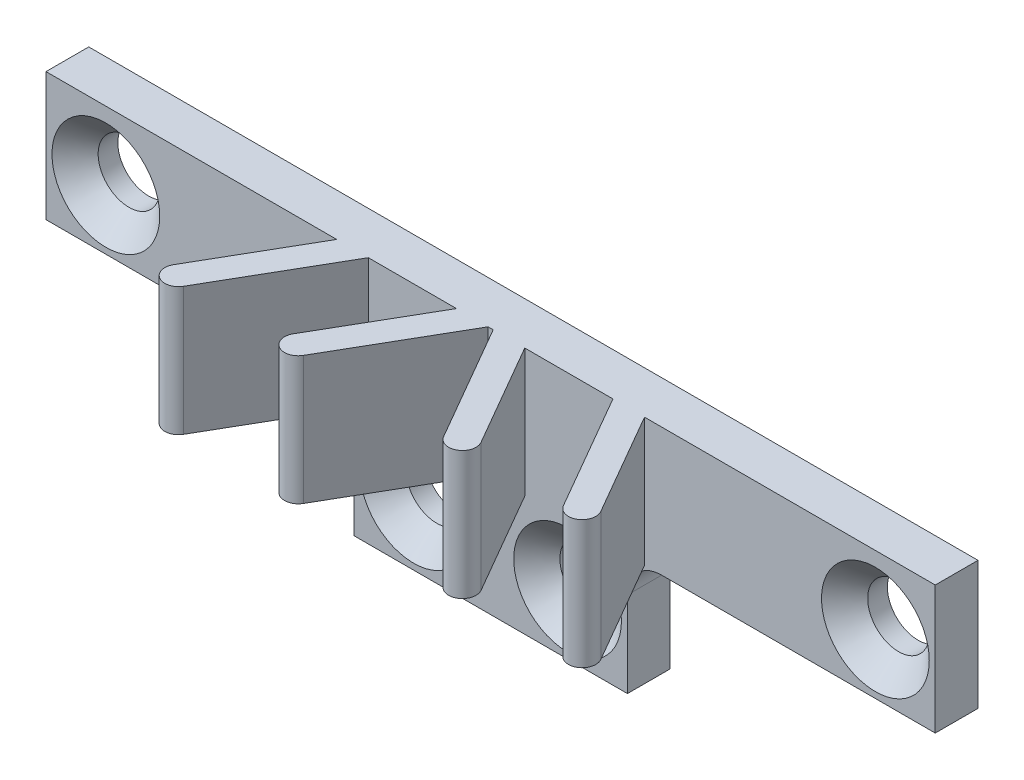
SolidWorks part; units mm, degrees
material "POLYURETHANE (11671)"
ref_plane "Front Plane" through (0, 0, 0) normal (0, 0, 1) x (1, 0, 0)
ref_plane "Top Plane" through (0, 0, 0) normal (0, 1, 0) x (1, 0, 0)
ref_plane "Right Plane" through (0, 0, 0) normal (1, 0, 0) x (0, 0, -1)
sketch "Sketch1" plane through (0, 0, 0) normal (0, 0, 1) x (1, 0, 0)
  line L20 (26, 7.25) -> (26, -0.25)
  line L21 (8, -7.25) -> (-8, -7.25)
  line L22 (-8, -7.25) -> (-8, -0.25)
  line L23 (-8, -0.25) -> (-26, -0.25)
  line L24 (-26, -0.25) -> (-26, 7.25)
  line L25 (-26, 7.25) -> (26, 7.25)
  line L27 (8, -7.25) -> (8, -0.25)
  line L28 (8, -0.25) -> (26, -0.25)
  line L29 (0, -55) -> (0, 55) construction
  line L30 (0, -7.25) -> (0, 7.25) construction
  line L32 (55, 0) -> (-55, 0) construction
  point P14 (0, 0)
  point P15 (0, -7.25)
  dimension "D1" = 52
  dimension "D2" = 7.5
  dimension "D3" = 16
  dimension "D4" = 7
extrude "Boss-Extrude1" add sketch "Sketch1" along normal mid plane 10
sketch "Sketch2" plane through (0, 0, 5) normal (0, 0, 1) x (1, 0, 0)
  line L5 (-8, -0.25) -> (8, -0.25)
  line L6 (-8, -0.25) -> (-8, -7.25)
  line L7 (-8, -7.25) -> (8, -7.25)
  line L8 (8, -0.25) -> (8, -7.25)
  line L13 (8, -0.25) -> (26, -0.25) construction
  line L14 (26, 7.25) -> (19, 7.25)
  line L15 (26, 7.25) -> (26, -0.25)
  line L16 (26, -0.25) -> (19, -0.25)
  line L17 (19, 7.25) -> (19, -0.25)
  line L18 (-8, -7.25) -> (8, -7.25) construction
  line L19 (8, -7.25) -> (8, -0.25) construction
  line L20 (-26, -0.25) -> (-8, -0.25) construction
  line L21 (-26, 7.25) -> (-19, 7.25)
  line L22 (-26, 7.25) -> (-26, -0.25)
  line L23 (-26, -0.25) -> (-19, -0.25)
  line L24 (-19, 7.25) -> (-19, -0.25)
  dimension "D1" = 7
extrude "Cut-Extrude1" cut sketch "Sketch2" against normal blind 7.5
hole_wizard "CSK for M3 Countersunk Flat Head Screw1" positions "Sketch5" profile "Sketch4" countersink size "M3" standard "ISO"
sketch "Sketch5" plane through (0, 0, -2.5) normal (0, 0, 1) x (1, 0, 0)
  line L1 (-8, -7.25) -> (8, -7.25) construction
  line L2 (0, -55) -> (0, 55) construction
  line L3 (-26, 7.25) -> (-26, -0.25) construction
  line L4 (26, -0.25) -> (26, 7.25) construction
  line L5 (-26, -0.25) -> (-19, -0.25) construction
  point P4 (-4.5, -3.75)
  point P6 (4.5, -3.75)
  point P19 (-22.5, 3.25)
  point P21 (22.5, 3.25)
  dimension "D2" = 3.5
  dimension "D3" = 4.5
  dimension "D4" = 9
  dimension "D1" = 3.5
  dimension "D5" = 3.5
  dimension "D6" = 3.5
sketch "Sketch4" plane through (-4.5, -3.75, -2.5) normal (1, 0, 0) x (0, -1, 0)
  line L0 (0, 0) -> (0, 6.0815)
  line L1 (0, 6.0815) -> (1.8, 5)
  line L2 (1.8, 5) -> (1.8, 1.35)
  line L3 (1.8, 1.35) -> (3.15, 0)
  line L5 (3.15, 0) -> (0, 0)
  line L6 (-1.8, 1.35) -> (-3.15, 0) construction
  line L10 (0, 6.0815) -> (-1.8, 5) construction
  line L11 (0, -6.35) -> (0, 107.95) construction
  dimension "Hole Dia." = 3.6
  dimension "Hole Depth" = 5
  dimension "Near C'Sink Dia." = 6.3
  dimension "Near C'Sink Angle" = 90
  dimension "Drill Angle" = 118
fillet "Fillet1" radius 2 2 edges at (8, -0.25, -3.75) (-8, -0.25, -3.75)
sketch "Sketch6" plane through (0, 7.25, 0) normal (0, 1, 0) x (1, 0, 0)
  line L1 (12.4932, -3.5505) -> (13.3301, -5) construction
  line L8 (13.3301, -5) -> (11.4826, -5)
  line L9 (12.4932, -3.5505) -> (9, 2.5)
  line L35 (12.4932, -3.5505) -> (11.1076, -4.3505) construction
  line L36 (11.1076, -4.3505) -> (11.4826, -5) construction
  line L37 (19, -5) -> (-19, -5) construction
  line L38 (9, 2.5) -> (7.1525, 2.5) construction
  line L39 (7.1525, 2.5) -> (11.1076, -4.3505)
  line L40 (26, 2.5) -> (19, 2.5) construction
  line L41 (9, 2.5) -> (19, 2.5)
  line L42 (19, 2.5) -> (19, -5)
  line L43 (19, -5) -> (13.3301, -5)
  line L45 (1.9975, 2.5) -> (5.4908, -3.5505)
  line L46 (5.4908, -3.5505) -> (4.1051, -4.3505) construction
  line L47 (4.1051, -4.3505) -> (4.4801, -5) construction
  line L48 (4.1051, -4.3505) -> (0.15, 2.5)
  line L50 (-4.1051, -4.3505) -> (-5.4908, -3.5505) construction
  line L51 (-5.4908, -3.5505) -> (-1.9975, 2.5)
  line L52 (-4.1051, -4.3505) -> (-4.4801, -5)
  line L54 (0, -55) -> (0, 55) construction
  line L55 (11.4826, -5) -> (4.4801, -5)
  line L56 (19, 2.5) -> (19, -5) construction
  line L57 (7.1525, 2.5) -> (1.9975, 2.5)
  line L58 (4.4801, -5) -> (-19, -5)
  line L59 (-19, -5) -> (-19, 2.5)
  line L60 (-19, 2.5) -> (-26, 2.5) construction
  line L61 (-19, 2.5) -> (-19, -5) construction
  line L62 (-19, 2.5) -> (-9, 2.5)
  line L63 (0.15, 2.5) -> (-0.15, 2.5)
  line L64 (-0.15, 2.5) -> (-4.1051, -4.3505)
  line L65 (-12.4932, -3.5505) -> (-11.1076, -4.3505) construction
  line L66 (-12.4932, -3.5505) -> (-9, 2.5)
  line L67 (-7.1525, 2.5) -> (-11.1076, -4.3505)
  line L68 (-9, 2.5) -> (-7.1525, 2.5) construction
  line L69 (-7.1525, 2.5) -> (-1.9975, 2.5)
  arc A2 (12.4932, -3.5505) -> (11.1076, -4.3505) centre (11.8004, -3.9505) cw
  arc A3 (5.4908, -3.5505) -> (4.1051, -4.3505) centre (4.7979, -3.9505) cw
  arc A4 (-4.1051, -4.3505) -> (-5.4908, -3.5505) centre (-4.7979, -3.9505) cw
  arc A5 (-12.4932, -3.5505) -> (-11.1076, -4.3505) centre (-11.8004, -3.9505) ccw
  dimension "D4" = 0.8
  dimension "D1" = 1.6
  dimension "D2" = 0.75
  dimension "D3" = 60
  dimension "D5" = 0.75
  dimension "D8" = 0.75
  dimension "D9" = 1.6
  dimension "D11" = 9
  dimension "D7" = 60
  dimension "D10" = 60
  dimension "D6" = 0.15
  dimension "D12" = 0.15
extrude "Cut-Extrude2" cut sketch "Sketch6" against normal up to surface (7.5 mm away)
equation "\"D12@Sketch6\"=\"D6@Sketch6\""
equation "\"D3@Sketch5\"=\"D4@Sketch5\"/2"
